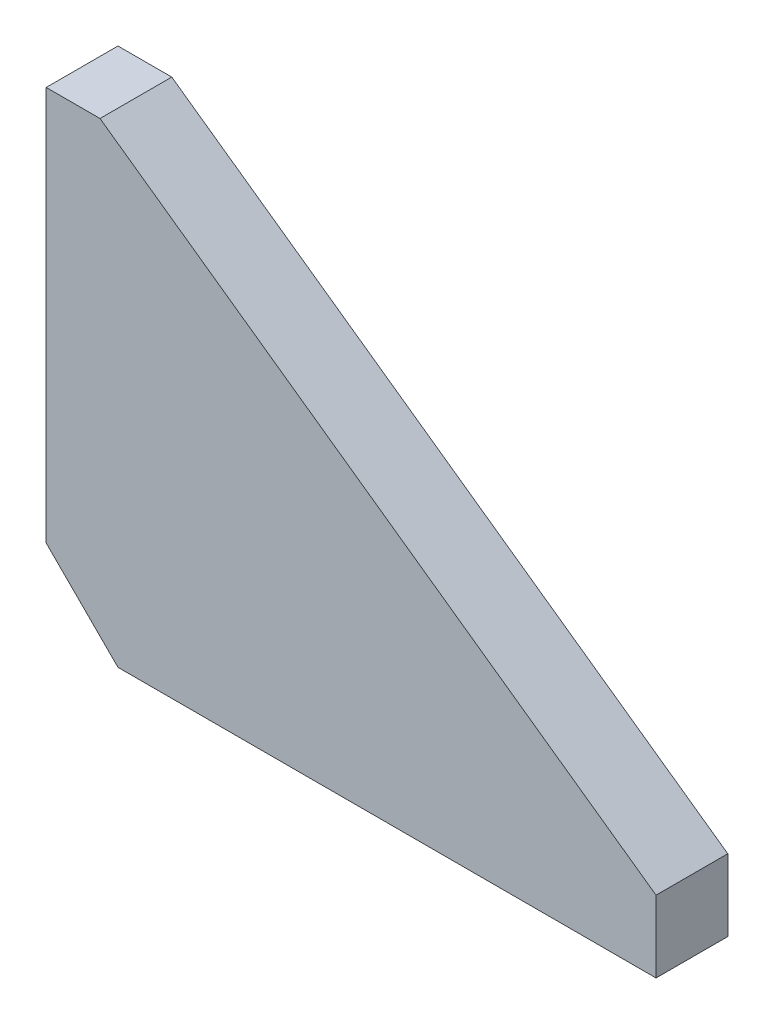
SolidWorks part; units mm, degrees
material "AISI 304"
ref_plane "Спереди" through (0, 0, 0) normal (0, 0, 1) x (1, 0, 0)
ref_plane "Сверху" through (0, 0, 0) normal (0, 1, 0) x (1, 0, 0)
ref_plane "Справа" through (0, 0, 0) normal (1, 0, 0) x (0, 0, -1)
sketch "Эскиз1" plane through (0, 0, 0) normal (0, 0, 1) x (1, 0, 0)
  line L0 (0, 0) -> (0, 52)
  line L1 (8, 52) -> (70, 8)
  line L2 (70, 0) -> (0, 0)
  line L3 (70, 0) -> (70, 8)
  line L4 (8, 52) -> (0, 52)
  dimension "D1" = 70
  dimension "D2" = 8
  dimension "D3" = 52
extrude "Бобышка-Вытянуть1" add sketch "Эскиз1" along normal mid plane 8
chamfer "Фаска1" distance 10 angle 45 1 edges at (0, 0, 0)
chamfer "Фаска2" distance 2 angle 45 2 edges at (0, 31, -4) (0, 31, 4)
chamfer "Фаска3" distance 2 angle 45 1 edges at (0, 52, 0)
